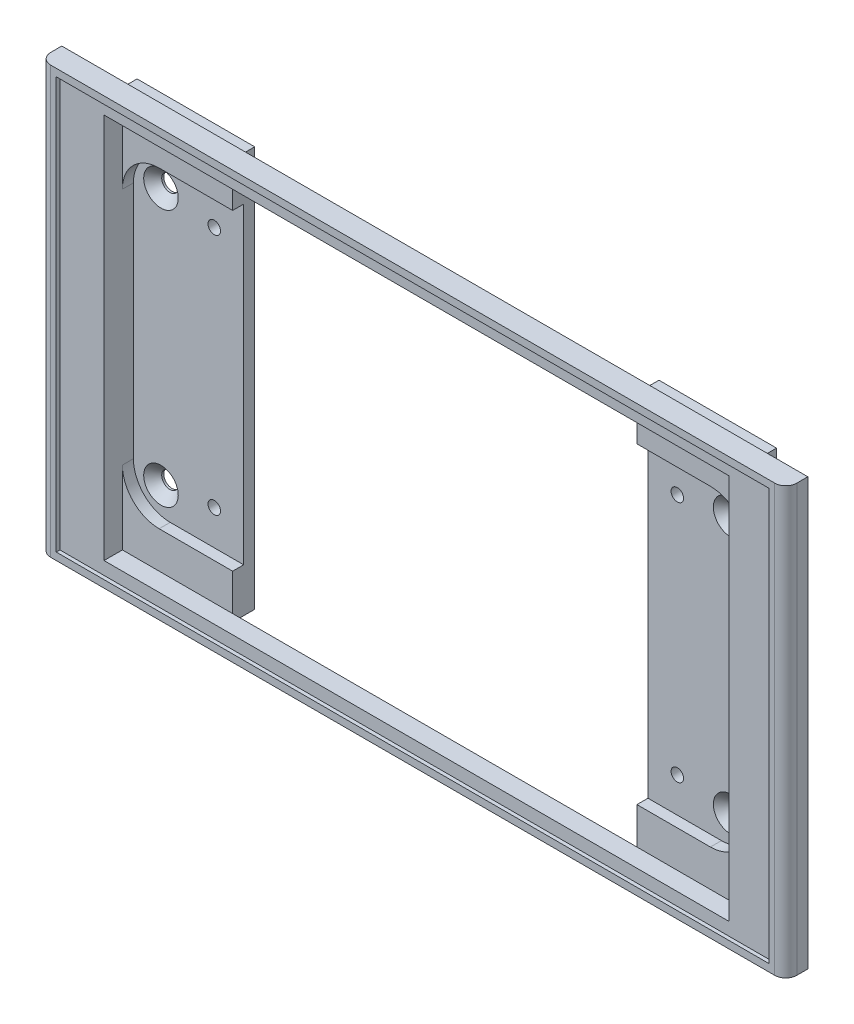
SolidWorks part; units mm, degrees
material "NYLON PRETO"
ref_plane "Frontal" through (0, 0, 0) normal (0, 0, 1) x (1, 0, 0)
ref_plane "Superior" through (0, 0, 0) normal (0, 1, 0) x (1, 0, 0)
ref_plane "Direito" through (0, 0, 0) normal (1, 0, 0) x (0, 0, -1)
sketch "Esboço1" plane through (0, 0, 0) normal (0, 0, 1) x (1, 0, 0)
  line L1 (-101.5, -58) -> (101.5, -58)
  line L2 (-101.5, -58) -> (-101.5, 58)
  line L3 (-101.5, 58) -> (101.5, 58)
  line L4 (101.5, -58) -> (101.5, 58)
  line L5 (0, 58) -> (0, -58) construction
  line L6 (-101.5, 0) -> (101.5, 0) construction
  point P0 (0, 0)
  dimension "D1" = 203
  dimension "D2" = 116
extrude "Ressalto-extrusão1" add sketch "Esboço1" along normal blind 6
sketch "Esboço2" plane through (0, 0, 6) normal (0, 0, 1) x (1, 0, 0)
  line L1 (-97, -56) -> (97, -56)
  line L2 (-97, -56) -> (-97, 56)
  line L3 (-97, 56) -> (97, 56)
  line L4 (97, -56) -> (97, 56)
  line L5 (0, 56) -> (0, -56) construction
  line L6 (-97, 0) -> (97, 0) construction
  point P0 (0, 0)
  dimension "D1" = 194
  dimension "D2" = 112
extrude "Corte-extrusão1" cut sketch "Esboço2" against normal blind 1
fillet "Filete2" radius 3 2 edges at (101.5, 0, 6) (-101.5, 0, 6)
sketch "Esboço3" plane through (0, 0, 5) normal (0, 0, -1) x (-1, 0, 0)
  line L1 (-87, -54.5) -> (87, -54.5)
  line L2 (-87, -54.5) -> (-87, 54.5)
  line L3 (-87, 54.5) -> (87, 54.5)
  line L4 (87, -54.5) -> (87, 54.5)
  line L5 (0, 54.5) -> (0, -54.5) construction
  line L6 (-87, 0) -> (87, 0) construction
  point P0 (0, 0)
  dimension "D1" = 174
  dimension "D2" = 109
extrude "Ressalto-extrusão2" add sketch "Esboço3" along normal blind 11
sketch "Esboço4" plane through (0, 0, -6) normal (0, 0, -1) x (-1, 0, 0)
  line L0 (87, 54.5) -> (-87, 54.5) construction
  line L1 (-55, -54.5) -> (55, -54.5)
  line L2 (-55, -54.5) -> (-55, 54.5)
  line L3 (-55, 54.5) -> (55, 54.5)
  line L4 (55, -54.5) -> (55, 54.5)
  line L5 (0, 54.5) -> (0, -54.5) construction
  line L6 (-55, 0) -> (55, 0) construction
  point P0 (0, 0)
  dimension "D1" = 110
extrude "Corte-extrusão2" cut sketch "Esboço4" against normal up to surface (6 mm away) up to face at (0, 0, 0)
sketch "Esboço5" plane through (0, 0, 5) normal (0, 0, 1) x (1, 0, 0)
  line L1 (-85, -52.5) -> (85, -52.5)
  line L2 (-85, -52.5) -> (-85, 52.5)
  line L3 (-85, 52.5) -> (85, 52.5)
  line L4 (85, -52.5) -> (85, 52.5)
  line L5 (0, 52.5) -> (0, -52.5) construction
  line L6 (-85, 0) -> (85, 0) construction
  point P0 (0, 0)
  dimension "D1" = 105
  dimension "D2" = 170
extrude "Corte-extrusão3" cut sketch "Esboço5" against normal blind 8 contours L3 L4 L1 L2
hole_wizard "Furo com folga de M31" positions "Esboço6" profile "Esboço7" hole size "M3" standard "DIN" end condition through all
sketch "Esboço6" plane through (0, 0, -6) normal (0, 0, -1) x (-1, 0, 0)
  line L0 (0, 52.5) -> (0, 0) construction
  line L1 (-55, 52.5) -> (55, 52.5) construction
  line L2 (0, 0) -> (-87, 0) construction
  line L3 (-87, 54.5) -> (-87, -54.5) construction
  point P0 (-63, 33)
  point P14 (63, 33)
  point P15 (63, -33)
  point P16 (-63, -33)
  dimension "D1" = 66
  dimension "D2" = 126
sketch "Esboço7" plane through (63, 33, -6) normal (1, 0, 0) x (0, 1, 0)
  line L0 (0, 0) -> (0, 12)
  line L1 (0, 12) -> (1.7, 12)
  line L2 (1.7, 12) -> (1.7, 0)
  line L5 (1.7, 0) -> (0, 0)
  line L11 (0, -6.35) -> (0, 107.95) construction
  dimension "Thru Hole Dia." = 3.4
  dimension "Thru Hole Depth" = 12
hole_wizard "Escareado para parafuso com cabeça escareada chata de M41" positions "Esboço8" profile "Esboço9" countersink size "M4" standard "DIN" end condition through all
sketch "Esboço8" plane through (0, 0, -3) normal (0, 0, 1) x (1, 0, 0)
  line L0 (0, 52.5) -> (0, 0) construction
  line L1 (-85, 52.5) -> (85, 52.5) construction
  line L2 (0, 0) -> (55, 0) construction
  line L3 (55, -52.5) -> (55, 52.5) construction
  point P0 (77.5, 35)
  point P15 (-77.5, 35)
  point P17 (77.5, -35)
  point P18 (-77.5, -35)
  dimension "D1" = 70
  dimension "D2" = 155
sketch "Esboço9" plane through (77.5, 35, -3) normal (1, 0, 0) x (0, -1, 0)
  line L0 (0, 0) -> (0, 3)
  line L1 (0, 3) -> (2.25, 3)
  line L2 (2.25, 3) -> (2.25, 2.45)
  line L3 (2.25, 2.45) -> (4.7, 0)
  line L5 (4.7, 0) -> (0, 0)
  line L6 (-2.25, 2.45) -> (-4.7, 0) construction
  line L11 (0, -6.35) -> (0, 107.95) construction
  dimension "Thru Hole Dia." = 4.5
  dimension "Thru Hole Depth" = 3
  dimension "Near C'Sink Dia." = 9.4
  dimension "Near C'Sink Angle" = 90
sketch "Esboço10" plane through (0, 0, -3) normal (0, 0, 1) x (1, 0, 0)
  line L0 (-55, 52.5) -> (-55, -52.5) construction
  line L1 (-85, 52.5) -> (-55, 52.5)
  line L2 (-85, 52.5) -> (-85, 42.5)
  line L3 (-85, 42.5) -> (-55, 42.5)
  line L4 (-55, 52.5) -> (-55, 42.5)
  line L5 (-85, 0) -> (0, 0) construction
  line L6 (-85, -52.5) -> (-85, 52.5) construction
  line L7 (0, 0) -> (0, 52.5) construction
  line L8 (-85, 52.5) -> (85, 52.5) construction
  line L9 (55, 52.5) -> (55, 42.5)
  line L10 (85, 42.5) -> (55, 42.5)
  line L11 (85, 52.5) -> (85, 42.5)
  line L12 (85, 52.5) -> (55, 52.5)
  line L13 (85, -52.5) -> (55, -52.5)
  line L14 (85, -52.5) -> (85, -42.5)
  line L15 (85, -42.5) -> (55, -42.5)
  line L16 (55, -52.5) -> (55, -42.5)
  line L17 (-55, -52.5) -> (-55, -42.5)
  line L18 (-85, -42.5) -> (-55, -42.5)
  line L19 (-85, -52.5) -> (-85, -42.5)
  line L20 (-85, -52.5) -> (-55, -52.5)
  dimension "D1" = 10
extrude "Ressalto-extrusão3" add sketch "Esboço10" along normal up to surface (3 mm away) up to face at (0, 0, 0)
fillet "Filete3" radius 10 4 edges at (85, -42.5, -1.5) (85, 42.5, -1.5) (-85, 42.5, -1.5) (-85, -42.5, -1.5)
fillet "Filete1" [suppressed] radius 6.5
